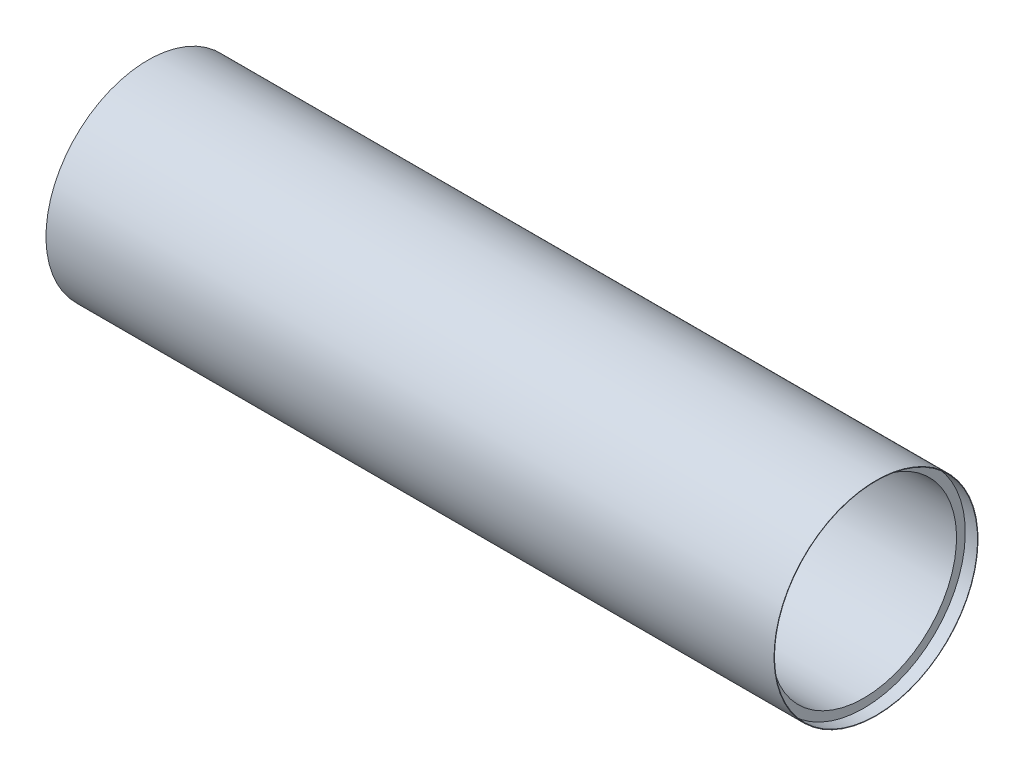
SolidWorks part; units mm, degrees
material "Carbon sandwich"
ref_plane "Front" through (0, 0, 0) normal (0, 0, 1) x (1, 0, 0)
ref_plane "Top" through (0, 0, 0) normal (0, 1, 0) x (1, 0, 0)
ref_plane "Right" through (0, 0, 0) normal (1, 0, 0) x (0, 0, -1)
sketch "Sketch1" plane through (0, 0, 0) normal (0, 0, 1) x (1, 0, 0)
  line L0 (39.1463, 83.9724) -> (49.3063, 83.9724)
  line L1 (49.3063, 83.9724) -> (49.3063, 76.7334)
  line L2 (49.3063, 76.7334) -> (631.0425, 76.7334)
  line L3 (631.0425, 76.7334) -> (631.0425, 83.9724)
  line L4 (631.0425, 83.9724) -> (641.2025, 83.9724)
  line L5 (641.2025, 83.9724) -> (641.2025, 84.3534)
  line L6 (641.2025, 84.3534) -> (39.1463, 84.3534)
  line L7 (39.1463, 84.3534) -> (39.1463, 83.9724)
  line L8 (0, 0) -> (134.0356, 0) construction
  dimension "D1" = 76.7334
  dimension "D2" = 0.381
  dimension "D3" = 10.16
  dimension "D4" = 10.16
  dimension "D5" = 581.7362
  dimension "D6" = 84.3534
  dimension "D7" = 0.381
revolve "Revolve1" add sketch "Sketch1" angle 360 about L8
